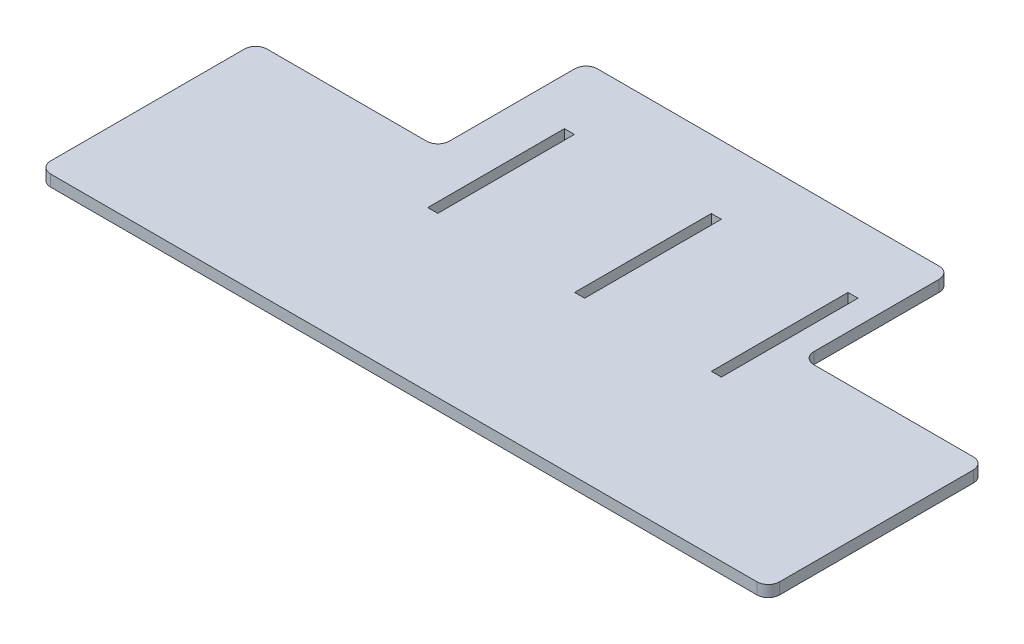
SolidWorks part; units mm, degrees
ref_plane "Front Plane" through (0, 0, 0) normal (0, 0, 1) x (1, 0, 0)
ref_plane "Top Plane" through (0, 0, 0) normal (0, 1, 0) x (1, 0, 0)
ref_plane "Right Plane" through (0, 0, 0) normal (1, 0, 0) x (0, 0, -1)
sketch "Sketch1" plane through (0, 0, 0) normal (0, 1, 0) x (1, 0, 0)
  line L0 (50.8, 30.1625) -> (101.6, 30.1625)
  line L1 (-101.6, -30.1625) -> (101.6, -30.1625)
  line L2 (-101.6, -30.1625) -> (-101.6, 30.1625)
  line L3 (-101.6, 30.1625) -> (-50.8, 30.1625)
  line L4 (101.6, -30.1625) -> (101.6, 30.1625)
  line L5 (-101.6, -30.1625) -> (101.6, 30.1625) construction
  line L6 (-101.6, 30.1625) -> (101.6, -30.1625) construction
  line L8 (-50.8, 30.1625) -> (-50.8, 71.4375)
  line L9 (-50.8, 71.4375) -> (50.8, 71.4375)
  line L10 (50.8, 30.1625) -> (50.8, 71.4375)
  point P0 (0, 0)
  dimension "D1" = 60.325
  dimension "D2" = 203.2
  dimension "D3" = 101.6
  dimension "D4" = 41.275
  dimension "D5" = 50.8
extrude "Boss-Extrude1" add sketch "Sketch1" along normal blind 3.175
sketch "Sketch2" plane through (0, 3.175, 0) normal (0, 1, 0) x (1, 0, 0)
  line L0 (-50.8, 71.4375) -> (-50.8, 30.1625) construction
  line L1 (3.175, 52.3875) -> (5.969, 52.3875)
  line L2 (3.175, 52.3875) -> (3.175, 14.2875)
  line L3 (3.175, 14.2875) -> (5.969, 14.2875)
  line L4 (5.969, 52.3875) -> (5.969, 14.2875)
  line L5 (50.8, 71.4375) -> (-50.8, 71.4375) construction
  dimension "D1" = 38.1
  dimension "D2" = 2.794
  dimension "D3" = 53.975
  dimension "D4" = 19.05
extrude "Cut-Extrude1" cut sketch "Sketch2" against normal blind 3.175
fillet "Fillet1" radius 3.175 8 edges at (-50.8, 1.5875, -71.4375) (-50.8, 1.5875, -30.1625) (-101.6, 1.5875, -30.1625) (-101.6, 1.5875, 30.1625) (101.6, 1.5875, 30.1625) (101.6, 1.5875, -30.1625) (50.8, 1.5875, -30.1625) (50.8, 1.5875, -71.4375)
sketch "Sketch3" plane through (0, 3.175, 0) normal (0, 1, 0) x (1, 0, 0)
  line L0 (47.625, 71.4375) -> (-47.625, 71.4375) construction
  line L1 (-37.7825, 14.2875) -> (-34.9885, 14.2875)
  line L2 (-37.7825, 14.2875) -> (-37.7825, 52.3875)
  line L3 (-37.7825, 52.3875) -> (-34.9885, 52.3875)
  line L4 (-34.9885, 14.2875) -> (-34.9885, 52.3875)
  line L5 (-50.8, 68.2625) -> (-50.8, 33.3375) construction
  dimension "D1" = 2.794
  dimension "D2" = 38.1
  dimension "D3" = 19.05
  dimension "D4" = 13.0175
extrude "Cut-Extrude2" cut sketch "Sketch3" against normal blind 9.525
sketch "Sketch4" plane through (0, 3.175, 0) normal (0, 1, 0) x (1, 0, 0)
  line L0 (47.625, 71.4375) -> (-47.625, 71.4375) construction
  line L1 (44.069, 52.3875) -> (41.275, 52.3875)
  line L2 (44.069, 52.3875) -> (44.069, 14.2875)
  line L3 (44.069, 14.2875) -> (41.275, 14.2875)
  line L4 (41.275, 52.3875) -> (41.275, 14.2875)
  line L6 (50.8, 33.3375) -> (50.8, 68.2625) construction
  dimension "D1" = 2.794
  dimension "D2" = 38.1
  dimension "D3" = 19.05
  dimension "D4" = 9.525
extrude "Cut-Extrude3" cut sketch "Sketch4" against normal blind 3.175
